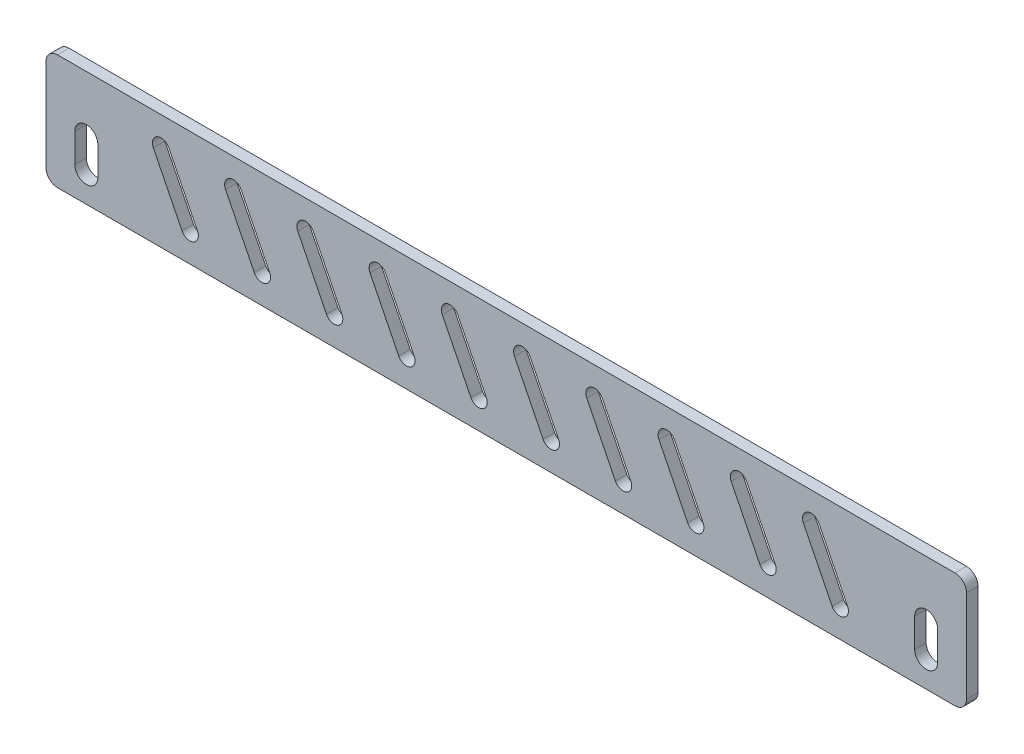
SolidWorks part; units mm, degrees
ref_plane "Front Plane" through (0, 0, 0) normal (0, 0, 1) x (1, 0, 0)
ref_plane "Top Plane" through (0, 0, 0) normal (0, 1, 0) x (1, 0, 0)
ref_plane "Right Plane" through (0, 0, 0) normal (1, 0, 0) x (0, 0, -1)
sketch "Sketch1" plane through (0, 0, 0) normal (0, 0, 1) x (1, 0, 0)
  line L1 (-80, 10) -> (80, 10)
  line L2 (-80, 10) -> (-80, -10)
  line L3 (-80, -10) -> (80, -10)
  line L4 (80, 10) -> (80, -10)
  line L5 (-80, 10) -> (80, -10) construction
  line L6 (-80, -10) -> (80, 10) construction
  point P0 (0, 0)
  dimension "D1" = 20
  dimension "D2" = 160
extrude "Boss-Extrude1" add sketch "Sketch1" along normal blind 2
fillet "Fillet1" radius 2 4 edges at (80, -10, 1) (80, 10, 1) (-80, -10, 1) (-80, 10, 1)
sketch "Sketch2" plane through (0, 0, 2) normal (0, 0, 1) x (1, 0, 0)
  line L0 (-72.995, 0) -> (-72.995, -5) construction
  line L1 (-70.99, 0) -> (-70.99, -5)
  line L2 (-75, 0) -> (-75, -5)
  line L3 (-80, 8) -> (-80, -8) construction
  line L6 (0, 28.6313) -> (0, -28.6313) construction
  line L7 (72.995, 0) -> (72.995, -5) construction
  line L8 (70.99, 0) -> (70.99, -5)
  line L9 (75, 0) -> (75, -5)
  line L10 (78, 10) -> (-78, 10) construction
  line L11 (-78, -10) -> (78, -10) construction
  arc A0 (-70.99, 0) -> (-75, 0) centre (-72.995, 0) ccw
  arc A1 (-75, -5) -> (-70.99, -5) centre (-72.995, -5) ccw
  arc A2 (70.99, 0) -> (75, 0) centre (72.995, 0) cw
  arc A3 (75, -5) -> (70.99, -5) centre (72.995, -5) cw
  point P2 (-72.995, -2.5)
  point P17 (0, 0)
  point P20 (72.995, -2.5)
  dimension "D3" = 10
  dimension "D4" = 5
  dimension "D1" = 4.01
  dimension "D2" = 5
extrude "Cut-Extrude1" cut sketch "Sketch2" against normal through all
sketch "Sketch3" plane through (0, 0, 2) normal (0, 0, 1) x (1, 0, 0)
  line L0 (-60, 5) -> (-55.0211, -5) construction
  line L1 (-58.6572, 5.6685) -> (-53.6784, -4.3315)
  line L2 (-61.3428, 4.3315) -> (-56.3639, -5.6685)
  line L3 (78, 10) -> (-78, 10) construction
  line L4 (-78, -10) -> (78, -10) construction
  line L5 (-80, 8) -> (-80, -8) construction
  line L6 (-47.4444, 5) -> (-42.4656, -5) construction
  line L7 (-46.1017, 5.6685) -> (-41.1228, -4.3315)
  line L8 (-48.7872, 4.3315) -> (-43.8084, -5.6685)
  line L9 (-34.8889, 5) -> (-29.91, -5) construction
  line L10 (-33.5461, 5.6685) -> (-28.5673, -4.3315)
  line L11 (-36.2317, 4.3315) -> (-31.2528, -5.6685)
  line L12 (-22.3333, 5) -> (-17.3545, -5) construction
  line L13 (-20.9906, 5.6685) -> (-16.0117, -4.3315)
  line L14 (-23.6761, 4.3315) -> (-18.6973, -5.6685)
  line L15 (-9.7778, 5) -> (-4.7989, -5) construction
  line L16 (-8.435, 5.6685) -> (-3.4562, -4.3315)
  line L17 (-11.1206, 4.3315) -> (-6.1417, -5.6685)
  line L18 (2.7778, 5) -> (7.7566, -5) construction
  line L19 (4.1206, 5.6685) -> (9.0994, -4.3315)
  line L20 (1.435, 4.3315) -> (6.4139, -5.6685)
  line L21 (15.3333, 5) -> (20.3122, -5) construction
  line L22 (16.6761, 5.6685) -> (21.655, -4.3315)
  line L23 (13.9906, 4.3315) -> (18.9694, -5.6685)
  line L24 (27.8889, 5) -> (32.8677, -5) construction
  line L25 (29.2317, 5.6685) -> (34.2105, -4.3315)
  line L26 (26.5461, 4.3315) -> (31.525, -5.6685)
  line L27 (40.4444, 5) -> (45.4233, -5) construction
  line L28 (41.7872, 5.6685) -> (46.7661, -4.3315)
  line L29 (39.1017, 4.3315) -> (44.0805, -5.6685)
  line L30 (53, 5) -> (57.9789, -5) construction
  line L31 (54.3428, 5.6685) -> (59.3216, -4.3315)
  line L32 (51.6572, 4.3315) -> (56.6361, -5.6685)
  line L33 (80, -8) -> (80, 8) construction
  arc A0 (-58.6572, 5.6685) -> (-61.3428, 4.3315) centre (-60, 5) ccw
  arc A1 (-56.3639, -5.6685) -> (-53.6784, -4.3315) centre (-55.0211, -5) ccw
  arc A2 (-46.1017, 5.6685) -> (-48.7872, 4.3315) centre (-47.4444, 5) ccw
  arc A3 (-43.8084, -5.6685) -> (-41.1228, -4.3315) centre (-42.4656, -5) ccw
  arc A4 (-33.5461, 5.6685) -> (-36.2317, 4.3315) centre (-34.8889, 5) ccw
  arc A5 (-31.2528, -5.6685) -> (-28.5673, -4.3315) centre (-29.91, -5) ccw
  arc A6 (-20.9906, 5.6685) -> (-23.6761, 4.3315) centre (-22.3333, 5) ccw
  arc A7 (-18.6973, -5.6685) -> (-16.0117, -4.3315) centre (-17.3545, -5) ccw
  arc A8 (-8.435, 5.6685) -> (-11.1206, 4.3315) centre (-9.7778, 5) ccw
  arc A9 (-6.1417, -5.6685) -> (-3.4562, -4.3315) centre (-4.7989, -5) ccw
  arc A10 (4.1206, 5.6685) -> (1.435, 4.3315) centre (2.7778, 5) ccw
  arc A11 (6.4139, -5.6685) -> (9.0994, -4.3315) centre (7.7566, -5) ccw
  arc A12 (16.6761, 5.6685) -> (13.9906, 4.3315) centre (15.3333, 5) ccw
  arc A13 (18.9694, -5.6685) -> (21.655, -4.3315) centre (20.3122, -5) ccw
  arc A14 (29.2317, 5.6685) -> (26.5461, 4.3315) centre (27.8889, 5) ccw
  arc A15 (31.525, -5.6685) -> (34.2105, -4.3315) centre (32.8677, -5) ccw
  arc A16 (41.7872, 5.6685) -> (39.1017, 4.3315) centre (40.4444, 5) ccw
  arc A17 (44.0805, -5.6685) -> (46.7661, -4.3315) centre (45.4233, -5) ccw
  arc A18 (54.3428, 5.6685) -> (51.6572, 4.3315) centre (53, 5) ccw
  arc A19 (56.6361, -5.6685) -> (59.3216, -4.3315) centre (57.9789, -5) ccw
  point P2 (-57.5106, 0)
  point P17 (-44.955, 0)
  point P24 (-32.3995, 0)
  point P31 (-19.8439, 0)
  point P38 (-7.2884, 0)
  point P45 (5.2672, 0)
  point P52 (17.8228, 0)
  point P59 (30.3783, 0)
  point P66 (42.9339, 0)
  point P73 (55.4894, 0)
  dimension "D4" = 1.5
  dimension "D1" = 5
  dimension "D2" = 5
  dimension "D3" = 20
  dimension "D5" = 63.532
  dimension "D7" = 22.0211
  dimension "D6" = 10
extrude "Cut-Extrude2" cut sketch "Sketch3" against normal blind 10
